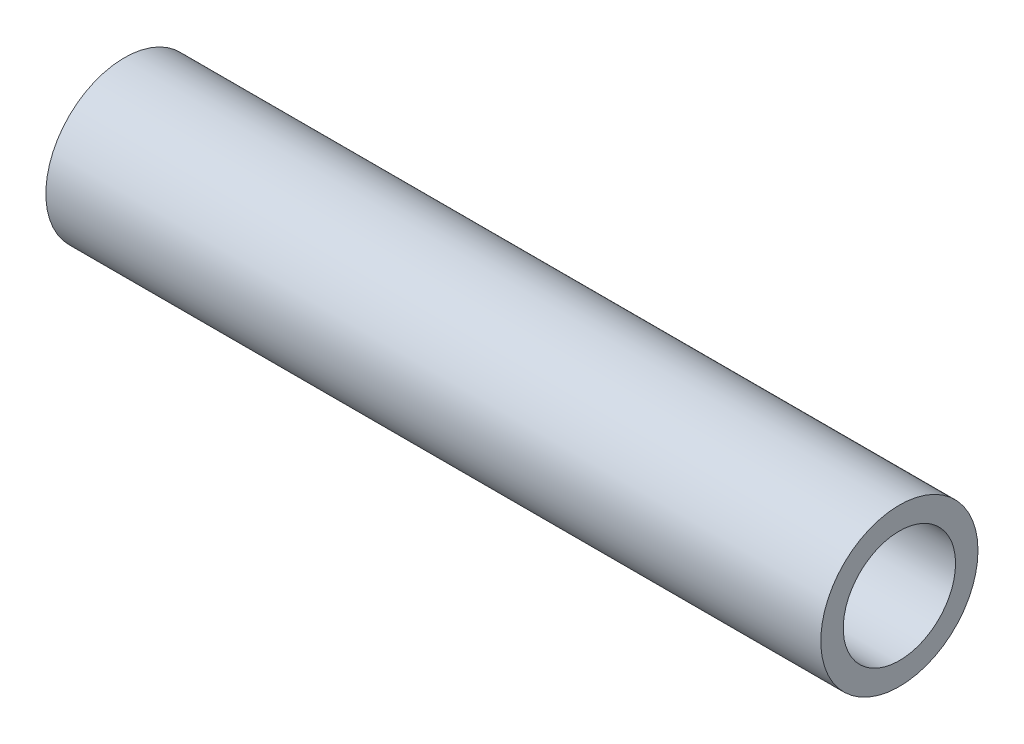
SolidWorks part; units mm, degrees
ref_plane "Front Plane" through (0, 0, 0) normal (1, 0, 0) x (0, 1, 0)
ref_plane "Top Plane" through (0, 0, 0) normal (0, 0, 1) x (0, 1, 0)
ref_plane "Right Plane" through (0, 0, 0) normal (0, 1, 0) x (-1, 0, 0)
sketch "Sketch1" plane through (0, 0, 0) normal (1, 0, 0) x (0, 1, 0)
  circle A0 centre (0, 0) radius 5
  circle A1 centre (0, 0) radius 7
  dimension "D1" = 14
  dimension "D2" = 10
extrude "Boss-Extrude1" add sketch "Sketch1" along normal blind 69
